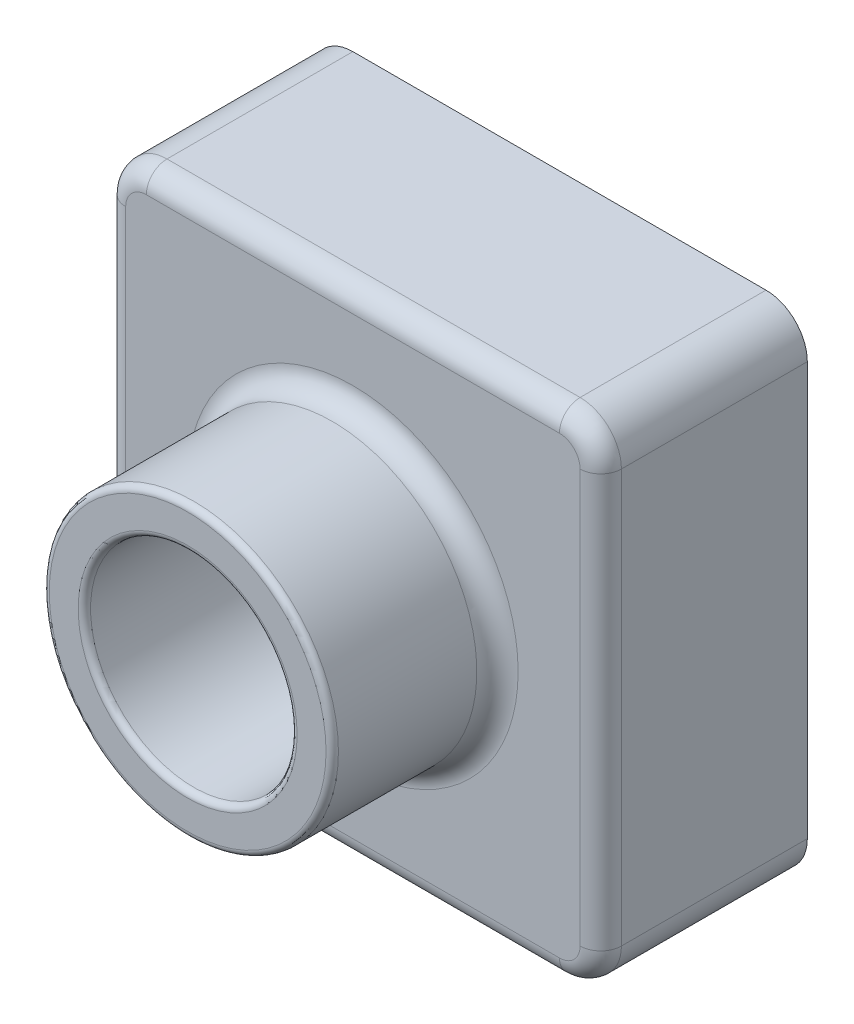
SolidWorks part; units mm, degrees
material "Chrome Stainless Steel"
ref_plane "Front Plane" through (0, 0, 0) normal (0, 0, 1) x (1, 0, 0)
ref_plane "Top Plane" through (0, 0, 0) normal (0, 1, 0) x (1, 0, 0)
ref_plane "Right Plane" through (0, 0, 0) normal (1, 0, 0) x (0, 0, -1)
sketch "Sketch1" plane through (0, 0, 0) normal (0, 0, 1) x (1, 0, 0)
  line L1 (0, 0) -> (120, 0)
  line L2 (0, 0) -> (0, 120)
  line L3 (0, 120) -> (120, 120)
  line L4 (120, 0) -> (120, 120)
  dimension "D1" = 120
  dimension "D2" = 120
extrude "Boss-Extrude1" add sketch "Sketch1" along normal blind 50
sketch "Sketch2" plane through (0, 0, 50) normal (0, 0, 1) x (1, 0, 0)
  line L0 (120, 120) -> (0, 120) construction
  line L1 (120, 0) -> (120, 120) construction
  circle A0 centre (60, 60) radius 35
  dimension "D1" = 70
  dimension "D2" = 60
  dimension "D3" = 60
extrude "Boss-Extrude2" add sketch "Sketch2" along normal blind 40
sketch "Sketch3" plane through (0, 0, 90) normal (0, 0, 1) x (1, 0, 0)
  circle A0 centre (60, 60) radius 25
  dimension "D1" = 50
extrude "Cut-Extrude1" cut sketch "Sketch3" against normal through all
fillet "Fillet1" radius 10 4 edges at (0, 0, 25) (120, 0, 25) (120, 120, 25) (0, 120, 25)
fillet "Fillet2" radius 1.5 2 edges at (95, 60, 90) (85, 60, 90)
fillet "Fillet3" radius 5 9 edges at (25, 60, 50) (117.0711, 117.0711, 50) (120, 60, 50) (117.0711, 2.9289, 50) (60, 0, 50) (2.9289, 2.9289, 50) (0, 60, 50) (2.9289, 117.0711, 50) (60, 120, 50)
shell "Shell1" thickness 2
